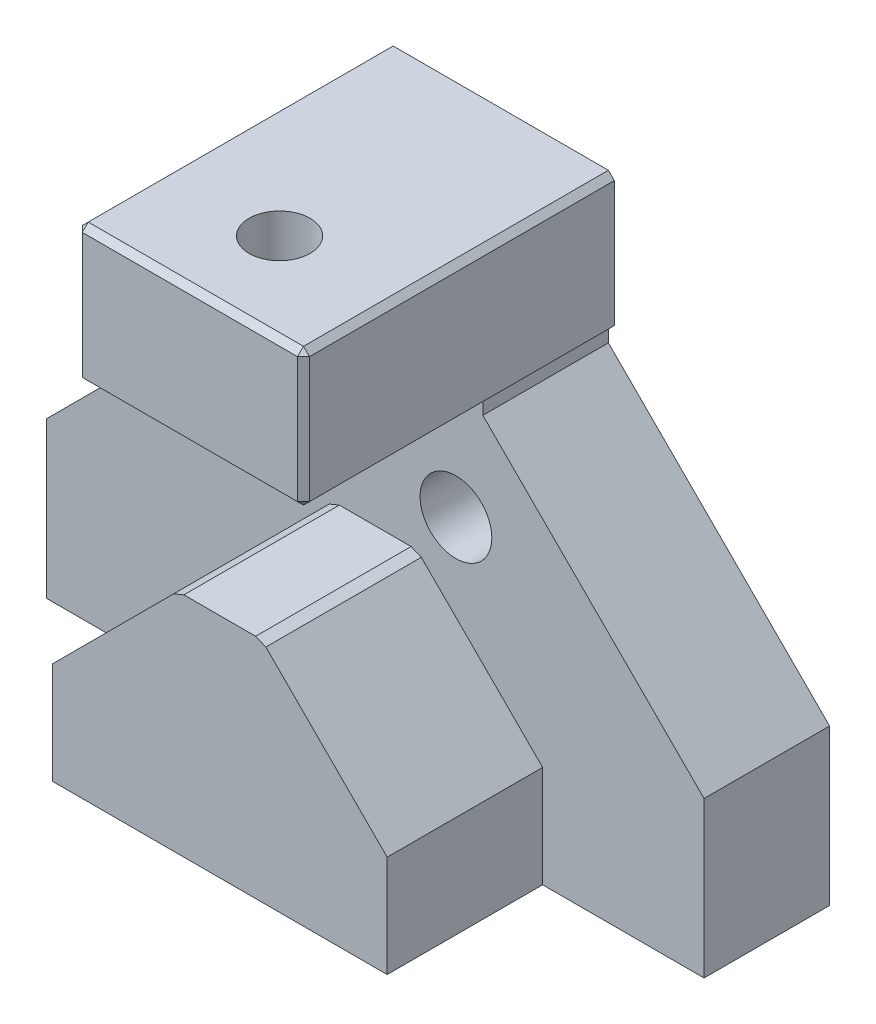
SolidWorks part; units mm, degrees
material "Plain Carbon Steel"
ref_plane "Front Plane" through (0, 0, 0) normal (0, 0, 1) x (1, 0, 0)
ref_plane "Top Plane" through (0, 0, 0) normal (0, 1, 0) x (1, 0, 0)
ref_plane "Right Plane" through (0, 0, 0) normal (1, 0, 0) x (0, 0, -1)
sketch "Sketch1" plane through (0, 0, 0) normal (0, 0, 1) x (1, 0, 0)
  line L0 (-19, 0) -> (19, 0)
  line L1 (19, 0) -> (19, -23)
  line L2 (19, -23) -> (18, -23)
  line L3 (18, -23) -> (18, -25)
  line L4 (18, -25) -> (55, -62)
  line L5 (55, -62) -> (55, -88)
  line L6 (55, -88) -> (-55, -88)
  line L7 (0, 0) -> (0, -46.3287) construction
  line L8 (-55, -62) -> (-55, -88)
  line L9 (-18, -25) -> (-55, -62)
  line L10 (-18, -23) -> (-18, -25)
  line L11 (-19, -23) -> (-18, -23)
  line L12 (-19, 0) -> (-19, -23)
  point P12 (0, -88)
  dimension "D1" = 38
  dimension "D2" = 110
  dimension "D3" = 26
  dimension "D4" = 88
  dimension "D5" = 65
  dimension "D6" = 45
  dimension "D7" = 1
extrude "Boss-Extrude1" add sketch "Sketch1" along normal blind 21
sketch "Sketch2" plane through (0, 0, 0) normal (0, 0, -1) x (-1, 0, 0)
  line L1 (-19, 0) -> (19, 0)
  line L2 (-19, 0) -> (-19, -23)
  line L3 (-19, -23) -> (19, -23)
  line L4 (19, 0) -> (19, -23)
extrude "Boss-Extrude2" add sketch "Sketch2" against normal blind 52
sketch "Sketch3" plane through (0, 0, 21) normal (0, 0, 1) x (1, 0, 0)
  line L0 (0, 0) -> (0, -96.2523) construction
  line L1 (-7, -50) -> (7, -50)
  line L2 (7, -50) -> (28, -71)
  line L3 (28, -71) -> (28, -88)
  line L4 (-55, -88) -> (55, -88) construction
  line L5 (28, -88) -> (-28, -88)
  line L6 (-28, -71) -> (-28, -88)
  line L7 (-7, -50) -> (-28, -71)
  point P11 (0, -88)
  point P13 (0, -50)
  dimension "D1" = 38
  dimension "D2" = 56
  dimension "D3" = 17
  dimension "D4" = 45
extrude "Boss-Extrude3" add sketch "Sketch3" along normal blind 26
chamfer "Chamfer1" distance 1 angle 45 8 edges at (0, -23, 52) (-19, -23, 26) (-19, -11.5, 52) (19, -23, 26) (19, -11.5, 52) (19, 0, 26) (0, 0, 52) (-19, 0, 26)
hole_wizard "M12 Tapped Hole1" positions "Sketch4" profile "Sketch5" tap size "M12" standard "ISO"
sketch "Sketch4" plane through (0, 0, 0) normal (0, 1, 0) x (1, 0, 0)
  line L0 (18, 0) -> (-18, 0) construction
  point P0 (0, -37)
  dimension "D1" = 37
sketch "Sketch5" plane through (0, 0, 37) normal (1, 0, 0) x (0, 0, 1)
  line L0 (0, 0) -> (0, 23)
  line L1 (0, 23) -> (5.1, 23)
  line L2 (5.1, 23) -> (5.1, 0)
  line L5 (5.1, 0) -> (0, 0)
  line L11 (0, -6.35) -> (0, 107.95) construction
  dimension "Thru Tap Drill Dia." = 10.2
  dimension "Thru Tap Drill Depth" = 23
cosmetic thread "Hole Thread1" parameters "D2"=12
hole_wizard "Ø12.0 (12) Diameter Hole1" positions "Sketch6" profile "Sketch7" hole size "Ø12.0" standard "ISO" end condition through all
sketch "Sketch6" plane through (0, 0, 21) normal (0, 0, 1) x (1, 0, 0)
  line L0 (0, 0) -> (0, -46.5126) construction
  line L2 (7, -50) -> (-7, -50) construction
  point P0 (-13.5, -42)
  point P2 (13.5, -42)
  dimension "D1" = 27
  dimension "D2" = 8
sketch "Sketch7" plane through (-13.5, -42, 21) normal (1, 0, 0) x (0, -1, 0)
  line L0 (0, 0) -> (0, 21)
  line L1 (0, 21) -> (6, 21)
  line L2 (6, 21) -> (6, 0)
  line L5 (6, 0) -> (0, 0)
  line L11 (0, -6.35) -> (0, 107.95) construction
  dimension "Thru Hole Dia." = 12
  dimension "Thru Hole Depth" = 21
chamfer "Chamfer2" distance 1 2 edges at (-7, -50, 34) (7, -50, 34)
